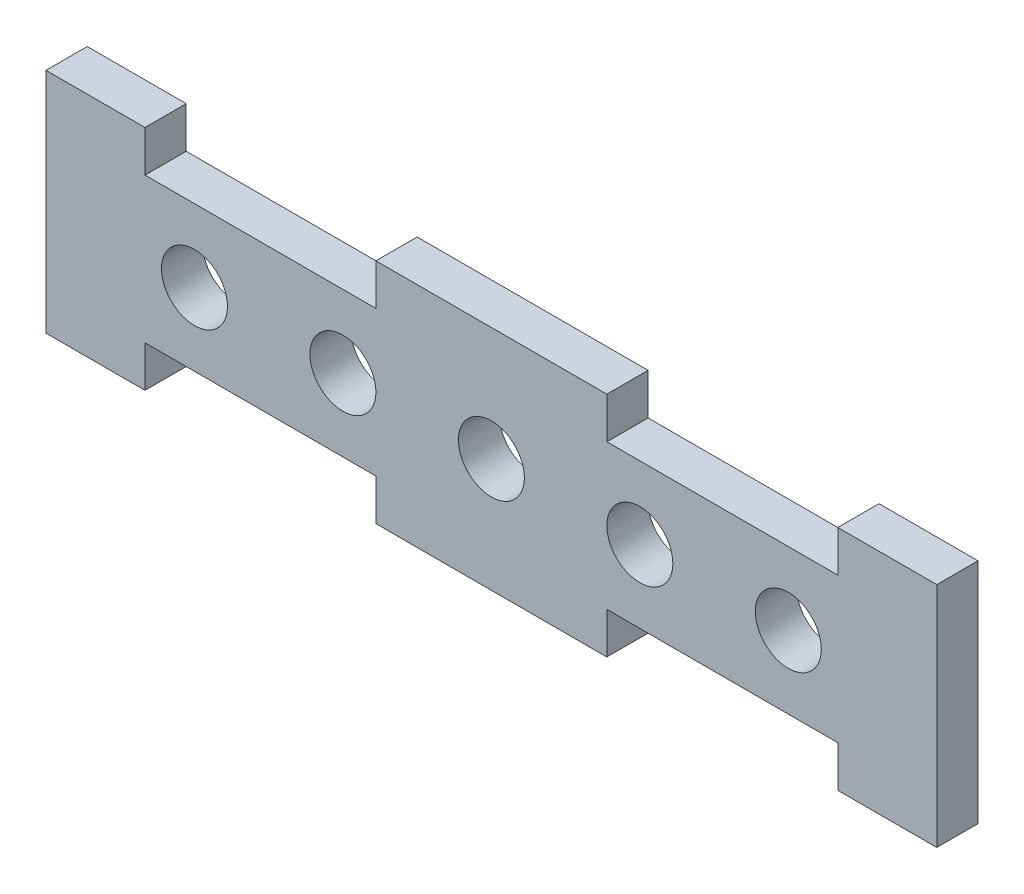
SolidWorks part; units mm, degrees
material "Oak"
ref_plane "Front Plane" through (0, 0, 0) normal (0, 0, 1) x (1, 0, 0)
ref_plane "Top Plane" through (0, 0, 0) normal (0, 1, 0) x (1, 0, 0)
ref_plane "Right Plane" through (0, 0, 0) normal (1, 0, 0) x (0, 0, -1)
sketch "Sketch1" plane through (0, 0, 0) normal (0, 0, 1) x (1, 0, 0)
  line L1 (0, 0) -> (76.2, 0)
  line L2 (0, 0) -> (0, -17.526)
  line L3 (0, -17.526) -> (76.2, -17.526)
  line L4 (76.2, 0) -> (76.2, -17.526)
extrude "Boss-Extrude1" add sketch "Sketch1" along normal blind 3.175
sketch "Sketch2" plane through (0, 0, 3.175) normal (0, 0, 1) x (1, 0, 0)
  line L0 (76.2, 0) -> (0, 0) construction
  line L1 (11.43, 0) -> (29.21, 0)
  line L2 (11.43, 0) -> (11.43, -3.175)
  line L3 (11.43, -3.175) -> (29.21, -3.175)
  line L4 (29.21, 0) -> (29.21, -3.175)
extrude "Cut-Extrude1" cut sketch "Sketch2" against normal through all
ref_plane "Plane1" through (0, -8.763, 0) normal (0, 1, 0) x (1, 0, 0)
ref_plane "Plane2" through (38.1, 0, 0) normal (1, 0, 0) x (0, 0, -1)
mirror "Mirror1" about plane through (0, -8.763, 0) normal (0, 1, 0) of "Cut-Extrude1"
mirror "Mirror2" about plane through (38.1, 0, 0) normal (1, 0, 0) of "Mirror1", "Cut-Extrude1"
hole_wizard "Hole1" positions "Sketch4" profile "Sketch3" legacy end condition through all
sketch "Sketch4" plane through (0, 0, 3.175) normal (0, 0, 1) x (1, 0, 0)
  line L0 (1.397, -8.763) -> (-1.397, -8.763) construction
  line L1 (38.1, -1.397) -> (38.1, 1.397) construction
  point P0 (15.24, -8.763)
  point P8 (38.1, -8.763)
  point P12 (26.67, -8.763)
  point P25 (49.53, -8.763)
  point P27 (60.96, -8.763)
sketch "Sketch3" plane through (15.24, -8.763, 3.175) normal (1, 0, 0) x (0, -1, 0)
  line L0 (0, 0) -> (0, 3.175)
  line L1 (0, 3.175) -> (2.54, 3.175)
  line L2 (2.54, 3.175) -> (2.54, 0)
  line L3 (2.54, 0) -> (0, 0)
  line L4 (0, 110) -> (0, -10) construction
  dimension "Diameter" = 5.08
  dimension "Depth" = 3.175
sketch "Sketch5" plane through (0, 0, 0) normal (-1, 0, 0) x (0, 0, 1)
  line L1 (0, 0) -> (3.175, 0)
  line L2 (0, 0) -> (0, -17.526)
  line L3 (0, -17.526) -> (3.175, -17.526)
  line L4 (3.175, 0) -> (3.175, -17.526)
extrude "Cut-Extrude2" cut sketch "Sketch5" against normal blind 3.81
sketch "Sketch6" plane through (76.2, 0, 0) normal (1, 0, 0) x (0, 0, -1)
  line L1 (0, 0) -> (-3.175, 0)
  line L2 (0, 0) -> (0, -17.526)
  line L3 (0, -17.526) -> (-3.175, -17.526)
  line L4 (-3.175, 0) -> (-3.175, -17.526)
extrude "Cut-Extrude3" cut sketch "Sketch6" against normal blind 3.81
